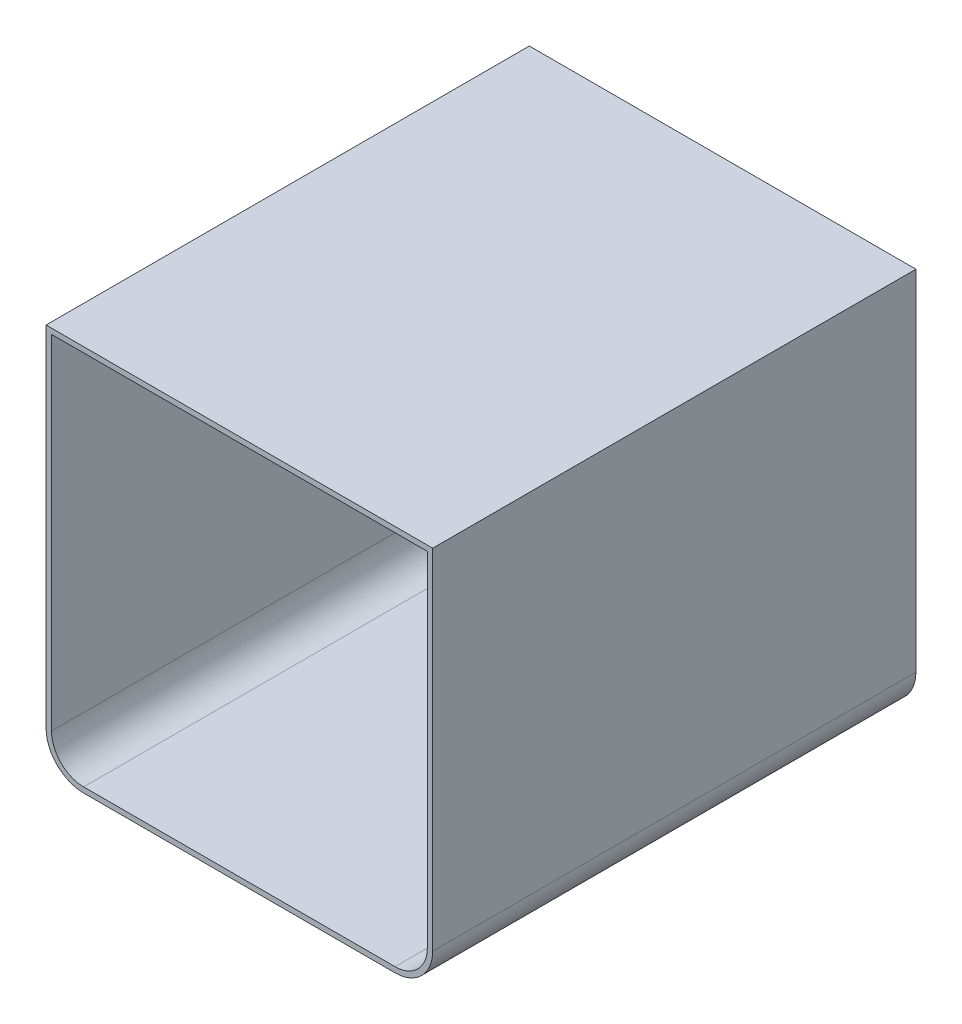
SolidWorks part; units mm, degrees
ref_plane "Front Plane" through (0, 0, 0) normal (0, 0, 1) x (1, 0, 0)
ref_plane "Top Plane" through (0, 0, 0) normal (0, 1, 0) x (1, 0, 0)
ref_plane "Right Plane" through (0, 0, 0) normal (1, 0, 0) x (0, 0, -1)
sketch "Sketch1" plane through (0, 0, 0) normal (0, 0, 1) x (1, 0, 0)
  line L0 (-70, -58) -> (-70, 70)
  line L1 (-58, -72) -> (58, -72)
  line L2 (-72, -58) -> (-72, 72)
  line L3 (-72, 72) -> (72, 72)
  line L4 (72, -58) -> (72, 72)
  line L5 (-72, -72) -> (72, 72) construction
  line L6 (-72, 72) -> (72, -72) construction
  line L7 (-70, 70) -> (70, 70)
  line L8 (70, -58) -> (70, 70)
  line L9 (-58, -70) -> (58, -70)
  arc A0 (58, -72) -> (72, -58) centre (58, -58) ccw
  arc A1 (-58, -72) -> (-72, -58) centre (-58, -58) cw
  arc A2 (58, -70) -> (70, -58) centre (58, -58) ccw
  arc A3 (-58, -70) -> (-70, -58) centre (-58, -58) cw
  point P0 (0, 0)
  dimension "D3" = 14
  dimension "D1" = 144
  dimension "D2" = 144
  dimension "D4" = 2
extrude "Boss-Extrude1" add sketch "Sketch1" along normal blind 180
